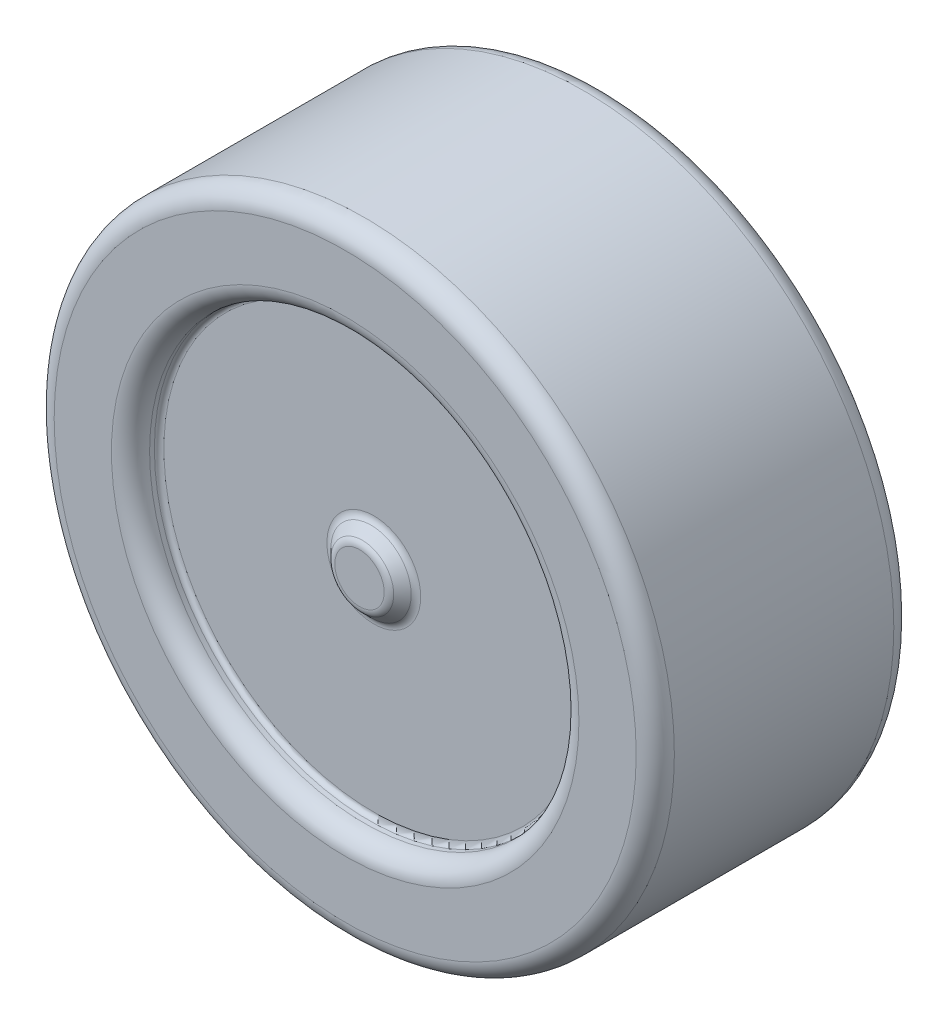
SolidWorks part; units mm, degrees
ref_plane "Front Plane" through (0, 0, 0) normal (0, 0, 1) x (1, 0, 0)
ref_plane "Top Plane" through (0, 0, 0) normal (0, 1, 0) x (1, 0, 0)
ref_plane "Right Plane" through (0, 0, 0) normal (1, 0, 0) x (0, 0, -1)
sketch "Sketch2" plane through (0, 0, 0) normal (0, 1, 0) x (1, 0, 0)
  line L0 (-24.5, 0) -> (-30.5, 0)
  line L1 (-32.5, 2) -> (-32.5, 25)
  line L2 (0, 0) -> (0, 20)
  line L3 (0, 20) -> (-6, 20)
  line L4 (-6, 20) -> (-6, 12)
  line L5 (-30.5, 27) -> (-24.5, 27)
  line L6 (-22.5, 25) -> (-22.5, 12)
  line L7 (-20.5, 10) -> (-8, 10)
  line L8 (-22.5, 2) -> (-22.5, 2.5)
  line L9 (0, 0) -> (0, 1.5)
  line L10 (0, 1.5) -> (-2.5858, 1.5)
  line L11 (-3.2929, 1.7929) -> (-4.2071, 2.7071)
  line L12 (-22, 3) -> (-4.9142, 3)
  arc A0 (-6, 12) -> (-8, 10) centre (-8, 12) cw
  arc A1 (-20.5, 10) -> (-22.5, 12) centre (-20.5, 12) cw
  arc A2 (-24.5, 27) -> (-22.5, 25) centre (-24.5, 25) cw
  arc A3 (-32.5, 25) -> (-30.5, 27) centre (-30.5, 25) cw
  arc A4 (-30.5, 0) -> (-32.5, 2) centre (-30.5, 2) cw
  arc A5 (-22.5, 2) -> (-24.5, 0) centre (-24.5, 2) cw
  arc A6 (-22.5, 2.5) -> (-22, 3) centre (-22, 2.5) cw
  arc A7 (-3.2929, 1.7929) -> (-2.5858, 1.5) centre (-2.5858, 2.5) ccw
  arc A8 (-4.2071, 2.7071) -> (-4.9142, 3) centre (-4.9142, 2) ccw
  point P11 (-6, 10)
  point P16 (-22.5, 27)
  point P19 (-32.5, 27)
  point P22 (-32.5, 0)
  point P30 (-22.5, 0)
  point P33 (-22.5, 3)
  point P36 (-3, 1.5)
  point P39 (-4.5, 3)
  dimension "D7" = 2
  dimension "D13" = 2
  dimension "D14" = 0.5
  dimension "D15" = 1
  dimension "D1" = 32.5
  dimension "D2" = 27
  dimension "D3" = 20
  dimension "D4" = 6
  dimension "D5" = 10
  dimension "D6" = 10
  dimension "D8" = 3
  dimension "D9" = 1.5
  dimension "D10" = 3
  dimension "D11" = 1.5
  dimension "D12" = 1.5
revolve "Revolve1" add sketch "Sketch2" angle 360 about L2
